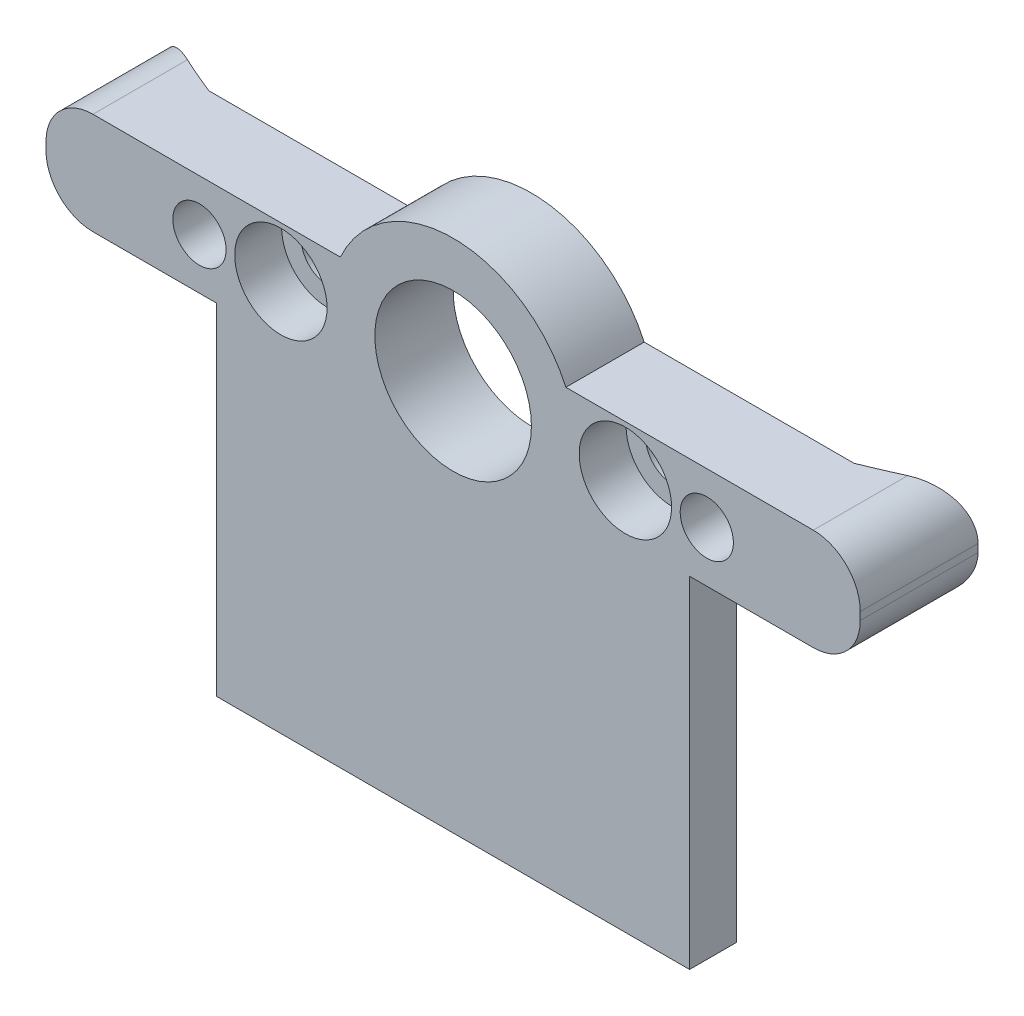
SolidWorks part; units mm, degrees
material "PLA"
ref_plane "Alzado" through (0, 0, 0) normal (0, 0, 1) x (1, 0, 0)
ref_plane "Planta" through (0, 0, 0) normal (0, 1, 0) x (1, 0, 0)
ref_plane "Vista lateral" through (0, 0, 0) normal (1, 0, 0) x (0, 0, -1)
sketch "Croquis1" plane through (0, 0, 0) normal (0, 0, 1) x (1, 0, 0)
  line L0 (-7.2005, 3.25) -> (-26, 3.25)
  line L1 (26, -3.25) -> (7.2005, -3.25)
  line L2 (26, -3.25) -> (26, 3.25)
  line L3 (26, 3.25) -> (7.2005, 3.25)
  line L4 (-26, -3.25) -> (-26, 3.25)
  line L5 (26, -3.25) -> (-26, 3.25) construction
  line L6 (26, 3.25) -> (-26, -3.25) construction
  line L9 (-7.2005, -3.25) -> (-26, -3.25)
  arc A0 (-7.2005, -3.25) -> (7.2005, -3.25) centre (0, 0) ccw
  circle A1 centre (0, 0) radius 5
  arc A2 (7.2005, 3.25) -> (-7.2005, 3.25) centre (0, 0) ccw
  dimension "D3" = 10
  dimension "D4" = 7.9
  dimension "D1" = 52
  dimension "D2" = 6.5
extrude "Saliente-Extruir1" add sketch "Croquis1" along normal blind 5
sketch "Croquis2" plane through (0, 0, 5) normal (0, 0, 1) x (1, 0, 0)
  line L0 (-11, 0) -> (11, 0) construction
  circle A0 centre (-11, 0) radius 1.7
  circle A1 centre (11, 0) radius 1.7
  point P2 (0, 0)
  dimension "D1" = 3.4
  dimension "D2" = 22
extrude "Cortar-Extruir1" cut sketch "Croquis2" against normal up to surface (5 mm away) up to face at (0, 0, 0)
sketch "Croquis3" plane through (0, 0, 5) normal (0, 0, 1) x (1, 0, 0)
  circle A0 centre (-11, 0) radius 2.95
  circle A1 centre (11, 0) radius 2.95
  dimension "D1" = 5.9
extrude "Cortar-Extruir2" cut sketch "Croquis3" against normal blind 3
sketch "Croquis4" plane through (0, 0, 0) normal (0, 1, 0) x (1, 0, 0)
  line L0 (-26, 0) -> (-20.6, 0)
  line L1 (-7.2005, 0) -> (-26, 0) construction
  line L2 (-26, 0) -> (-26, 2.52)
  arc A0 (-26, 2.52) -> (-20.6, 0) centre (-0.0755, 51.0269) ccw
  dimension "D1" = 55
  dimension "D2" = 2.52
  dimension "D3" = 5.4
extrude "Saliente-Extruir2" add sketch "Croquis4" along normal up to surface and the other way up to surface up to face at (-16.6003, 3.25, 2.5) other way up to face at (-16.6003, -3.25, 2.5)
sketch "Croquis5" plane through (0, 0, 5) normal (0, 0, 1) x (1, 0, 0)
  circle A0 centre (-16.2, 0) radius 1.7
  dimension "D2" = 3.4
  dimension "D1" = 16.2
extrude "Cortar-Extruir3" cut sketch "Croquis5" against normal blind 10
sketch "Croquis6" plane through (0, 0, 0) normal (0, 0, -1) x (-1, 0, 0)
  line L1 (19.55, 0) -> (17.875, 2.9012)
  line L2 (17.875, 2.9012) -> (14.525, 2.9012)
  line L3 (14.525, 2.9012) -> (12.85, 0)
  line L4 (12.85, 0) -> (14.525, -2.9012)
  line L5 (14.525, -2.9012) -> (17.875, -2.9012)
  line L6 (17.875, -2.9012) -> (19.55, 0)
  circle A0 centre (16.2, 0) radius 3.35 construction
  dimension "D1" = 3.35
extrude "Cortar-Extruir4" cut sketch "Croquis6" against normal blind 1.7 contours L4 L5 L6 L1 L2 L3
mirror "Simetría2" about plane through (0, 0, 0) normal (1, 0, 0) of "Cortar-Extruir4", "Cortar-Extruir3", "Saliente-Extruir2"
fillet "Redondeo1" radius 3 4 edges at (-26, -3.25, 1.24) (-26, 3.25, 1.24) (26, -3.25, 1.24) (26, 3.25, 1.24)
sketch "Croquis7" plane through (0, 0, 5) normal (0, 0, 1) x (1, 0, 0)
  line L0 (-23, -3.25) -> (-7.2005, -3.25) construction
  line L1 (-15.1003, -3.25) -> (-7.2005, -3.25)
  line L2 (-15.1003, -3.25) -> (-15.1003, -25)
  line L3 (-15.1003, -25) -> (15.1003, -25)
  line L4 (15.1003, -3.25) -> (15.1003, -25)
  line L5 (7.2005, -3.25) -> (23, -3.25) construction
  line L6 (7.2005, -3.25) -> (15.1003, -3.25)
  arc A1 (-7.2005, -3.25) -> (7.2005, -3.25) centre (0, 0) ccw construction
  arc A2 (-7.2005, -3.25) -> (7.2005, -3.25) centre (0, 0) ccw
  point P12 (0, -25)
  dimension "D1" = 25
extrude "Saliente-Extruir3" add sketch "Croquis7" against normal blind 2.5 contours L2 L3 L4 L6 A2 L1
sketch "Croquis8" plane through (0, -25, 0) normal (0, -1, 0) x (1, 0, 0)
  line L0 (-15.1003, 2.5) -> (-15.1003, 2)
  line L1 (-15.1003, 2.5) -> (-12.8003, 2.5)
  line L3 (0, 0) -> (0, 9.5214) construction
  line L4 (15.1003, 2.5) -> (12.8003, 2.5)
  line L5 (15.1003, 2.5) -> (15.1003, 2)
  arc A0 (-12.8003, 2.5) -> (-15.1003, 2) centre (-2.2693, -51.4824) ccw
  arc A1 (12.8003, 2.5) -> (15.1003, 2) centre (2.2693, -51.4824) cw
  dimension "D1" = 55
  dimension "D2" = 2.3
  dimension "D3" = 0.5
extrude "Saliente-Extruir4" add sketch "Croquis8" against normal up to surface (21.75 mm away) up to face at (-15.8868, -3.25, 1.9974)
